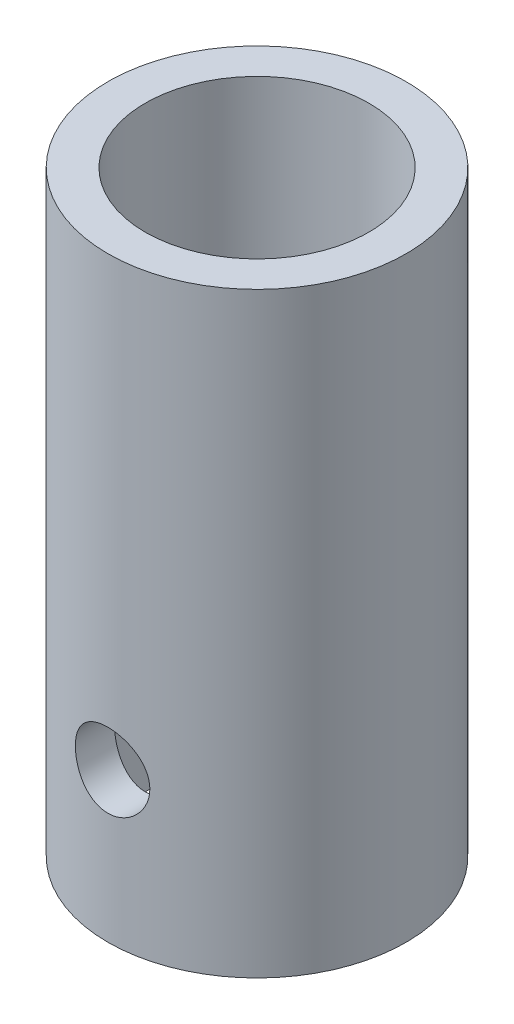
SolidWorks part; units mm, degrees
ref_plane "Front" through (0, 0, 0) normal (0, 0, 1) x (1, 0, 0)
ref_plane "Top" through (0, 0, 0) normal (0, 1, 0) x (1, 0, 0)
ref_plane "Right" through (0, 0, 0) normal (1, 0, 0) x (0, 0, -1)
sketch "Sketch1" plane through (0, 0, 0) normal (0, 1, 0) x (1, 0, 0)
  circle A0 centre (0, 0) radius 6.35
extrude "Boss-Extrude1" add sketch "Sketch1" along normal blind 25.4
sketch "Sketch3" plane through (0, 25.4, 0) normal (0, 1, 0) x (1, 0, 0)
  circle A0 centre (0, 0) radius 4.7625
extrude "Cut-Extrude1" cut sketch "Sketch3" against normal through all
hole_wizard "1/8 (0.125) Diameter Hole2" positions "3DSketch22" profile "Sketch17" hole size "1/8" standard "ANSI Inch"
sketch3d "3DSketch22"
  point P1 (-0.004, 6.3467, 6.35)
sketch "Sketch17" plane through (-0.004, 6.3467, 6.35) normal (0, 1, 0) x (1, 0, 0.0006)
  line L0 (0, 0) -> (0, 7.3029)
  line L1 (0, 7.3029) -> (1.5875, 6.349)
  line L2 (1.5875, 6.349) -> (1.5875, 0)
  line L5 (1.5875, 0) -> (0, 0)
  line L10 (0, 7.3029) -> (-1.5875, 6.349) construction
  line L11 (0, -6.35) -> (0, 107.95) construction
  dimension "Hole Dia." = 3.175
  dimension "Hole Depth" = 6.349
  dimension "Drill Angle" = 118
